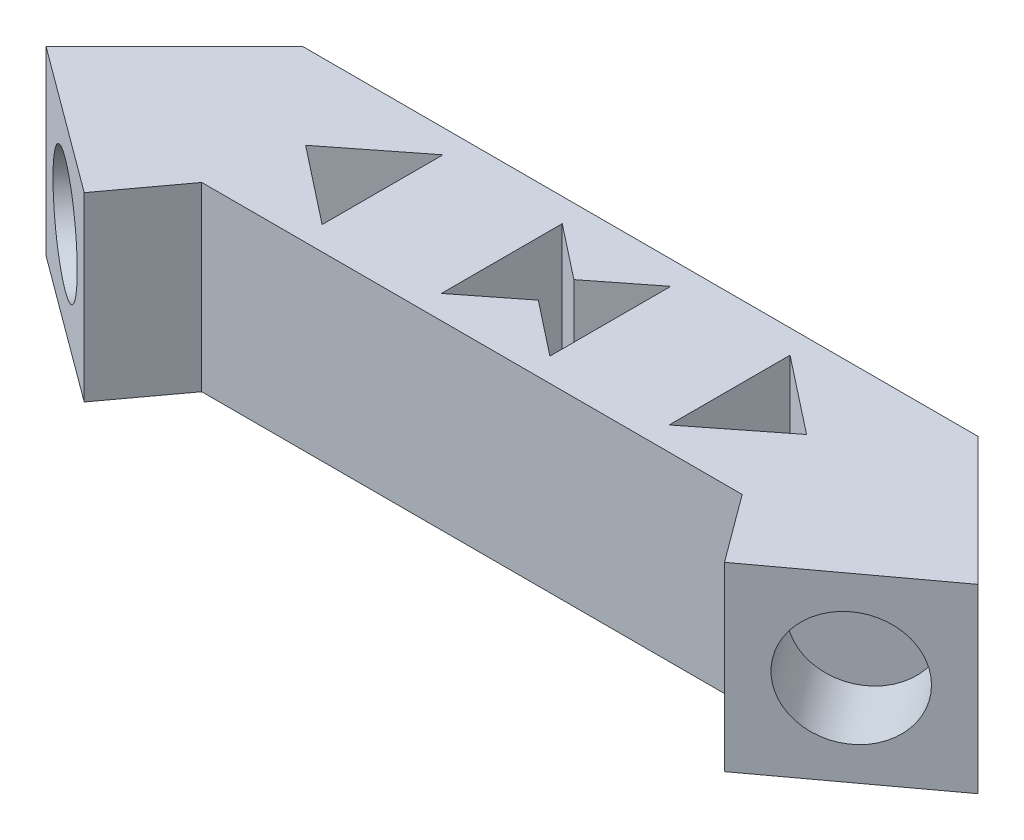
SolidWorks part; units mm, degrees
ref_plane "Front Plane" through (0, 0, 0) normal (0, 0, 1) x (1, 0, 0)
ref_plane "Top Plane" through (0, 0, 0) normal (0, 1, 0) x (1, 0, 0)
ref_plane "Right Plane" through (0, 0, 0) normal (1, 0, 0) x (0, 0, -1)
sketch "Sketch1" plane through (0, 0, 0) normal (0, 1, 0) x (1, 0, 0)
  line L1 (0, 0) -> (113.5797, 0)
  line L3 (-14.2032, 35.3536) -> (127.7828, 35.3536)
  line L5 (0, 0) -> (-10.4888, -14.2118)
  line L6 (-41.1439, 8.4129) -> (-10.4888, -14.2118)
  line L7 (56.7898, 35.3536) -> (56.7898, 0) construction
  line L8 (113.5797, 0) -> (124.0685, -14.2118)
  line L9 (154.7236, 8.4129) -> (124.0685, -14.2118)
  line L10 (127.7828, 35.3536) -> (154.7236, 8.4129)
  line L11 (-14.2032, 35.3536) -> (-41.1439, 8.4129)
  dimension "D1" = 141.986
  dimension "D2" = 135
  dimension "D3" = 38.1
  dimension "D4" = 38.1
  dimension "D5" = 10.4888
  dimension "D6" = 38.1
extrude "Boss-Extrude1" add sketch "Sketch1" along normal blind 38.1
sketch "Sketch2" plane through (-10.4888, 0, 14.2118) normal (-0.5938, 0, 0.8046) x (0.8046, 0, 0.5938)
  line L0 (-38.1, 38.1) -> (0, 0) construction
  line L1 (-38.1, 0) -> (0, 38.1) construction
  circle A0 centre (-19.05, 19.05) radius 12.065
  dimension "D1" = 24.13
extrude "Cut-Extrude1" cut sketch "Sketch2" against normal blind 15.24
sketch "Sketch3" plane through (50.5399, 0, 68.4787) normal (0.5938, 0, 0.8046) x (0.8046, 0, -0.5938)
  line L0 (91.3857, 38.1) -> (129.4857, 0) construction
  line L1 (91.3857, 0) -> (129.4857, 38.1) construction
  circle A0 centre (110.4357, 19.05) radius 12.065
  point P11 (110.4357, 19.05)
  dimension "D1" = 24.13
extrude "Cut-Extrude2" cut sketch "Sketch3" against normal blind 15.24
sketch "Sketch5" plane through (0, 38.1, 0) normal (0, 1, 0) x (1, 0, 0)
  line L0 (56.7898, 35.3536) -> (56.7898, 0) construction
  line L1 (127.7828, 35.3536) -> (-14.2032, 35.3536) construction
  line L2 (0, 0) -> (113.5797, 0) construction
  line L3 (2.7565, 17.6768) -> (45.3845, 17.6768) construction
  line L4 (4.1516, 17.6768) -> (20.32, 30.3768)
  line L5 (20.32, 30.3768) -> (20.32, 4.9768)
  line L6 (20.32, 4.9768) -> (4.1516, 17.6768)
  line L7 (32.8523, 35.3536) -> (32.8523, 0) construction
  line L8 (45.3845, 30.3768) -> (45.3845, 4.9768)
  line L11 (56.7898, 21.4182) -> (45.3845, 30.3768)
  line L12 (45.3845, 4.9768) -> (56.7898, 13.9355)
  line L13 (93.2597, 30.3768) -> (93.2597, 4.9768)
  line L14 (109.4281, 17.6768) -> (93.2597, 30.3768)
  line L15 (93.2597, 4.9768) -> (109.4281, 17.6768)
  line L16 (56.7898, 21.4182) -> (68.1951, 30.3768)
  line L17 (68.1951, 30.3768) -> (68.1951, 4.9768)
  line L18 (68.1951, 4.9768) -> (56.7898, 13.9355)
  line L19 (68.1951, 17.6768) -> (110.8231, 17.6768) construction
  dimension "D1" = 25.4
  dimension "D2" = 32.8523
  dimension "D3" = 38.149
  dimension "D4" = 20.32
  dimension "D5" = 42.628
  dimension "D6" = 42.628
  dimension "D7" = 17.6768
  dimension "D8" = 14.503
  dimension "D9" = 14.503
extrude "Cut-Extrude3" cut sketch "Sketch5" against normal blind 38.1
